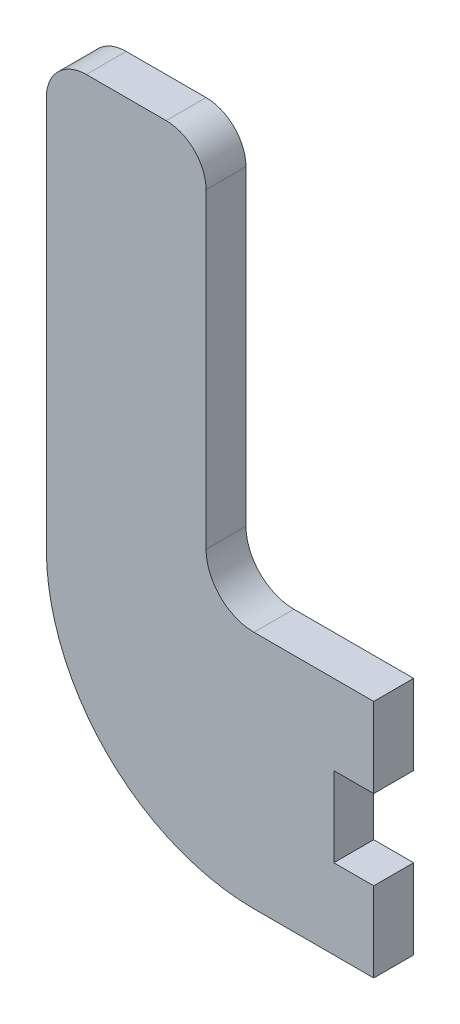
SolidWorks part; units mm, degrees
material "Acrylic (Medium-high impact)"
ref_plane "Front Plane" through (0, 0, 0) normal (0, 0, 1) x (1, 0, 0)
ref_plane "Top Plane" through (0, 0, 0) normal (0, 1, 0) x (1, 0, 0)
ref_plane "Right Plane" through (0, 0, 0) normal (1, 0, 0) x (0, 0, -1)
sketch "Sketch1" plane through (0, 0, 0) normal (0, 0, 1) x (1, 0, 0)
  line L0 (0, 0) -> (3.175, 0)
  line L1 (3.175, 0) -> (3.175, 6.35)
  line L2 (3.175, 6.35) -> (0, 6.35)
  line L3 (0, 6.35) -> (0, 12.7)
  line L4 (0, 12.7) -> (3.175, 12.7)
  line L5 (3.175, 12.7) -> (3.175, 19.05)
  line L6 (3.175, 19.05) -> (0, 19.05)
  line L7 (0, 0) -> (-6.35, 0)
  line L8 (-22.86, 16.51) -> (-22.86, 50.8)
  line L9 (-22.86, 50.8) -> (-10.16, 50.8)
  line L10 (-10.16, 22.86) -> (-10.16, 50.8)
  line L12 (0, 19.05) -> (-6.35, 19.05)
  arc A0 (-6.35, 0) -> (-22.86, 16.51) centre (-6.35, 16.51) cw
  arc A1 (-6.35, 19.05) -> (-10.16, 22.86) centre (-6.35, 22.86) cw
  dimension "D1" = 6.35
  dimension "D2" = 3.175
  dimension "D3" = 6.35
  dimension "D4" = 6.35
  dimension "D5" = 22.86
  dimension "D6" = 12.7
  dimension "D7" = 50.8
extrude "Boss-Extrude1" add sketch "Sketch1" along normal blind 3.175
fillet "Fillet1" radius 3.175 2 edges at (-10.16, 50.8, 1.5875) (-22.86, 50.8, 1.5875)
